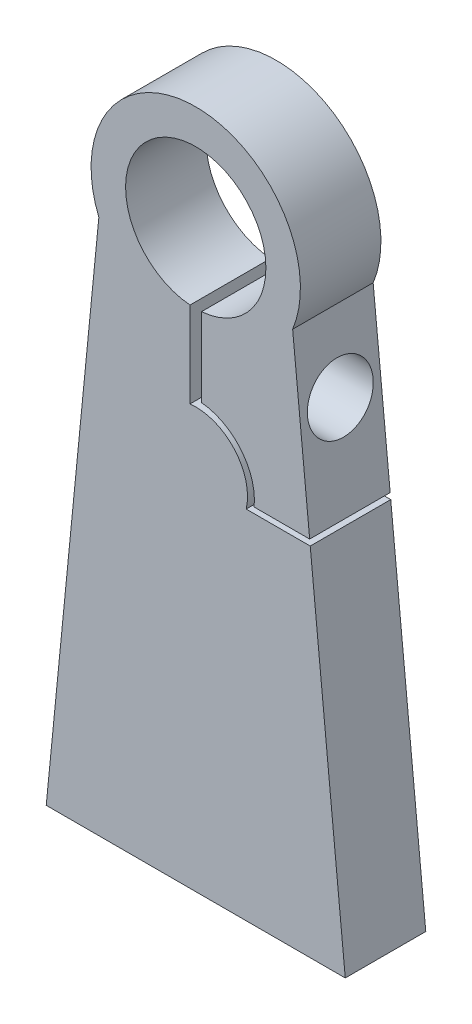
SolidWorks part; units mm, degrees
ref_plane "Front Plane" through (0, 0, 0) normal (0, 0, 1) x (1, 0, 0)
ref_plane "Top Plane" through (0, 0, 0) normal (0, 1, 0) x (1, 0, 0)
ref_plane "Right Plane" through (0, 0, 0) normal (1, 0, 0) x (0, 0, -1)
sketch "Sketch1" plane through (0, 0, 0) normal (0, 0, 1) x (1, 0, 0)
  line L0 (-13, -50) -> (13, -50)
  line L1 (-13, -50) -> (-8.4243, -3.441)
  line L2 (13, -50) -> (8.4243, -3.441)
  arc A0 (-8.4243, -3.441) -> (8.4243, -3.441) centre (0, 0) cw
  circle A1 centre (0, 0) radius 6.1
  dimension "D1" = 12.2
  dimension "D3" = 9.1
  dimension "D2" = 26
  dimension "D5" = 50
extrude "Thickness" add sketch "Sketch1" along normal mid plane 7
sketch "Sketch2" plane through (0, -50, 0) normal (0, -1, 0) x (1, 0, 0)
  line L0 (44.2539, 0) -> (-44.2539, 0) construction
  line L4 (-10.7909, 0) -> (-9.1454, -2.85)
  line L5 (-9.1454, -2.85) -> (-5.8546, -2.85)
  line L6 (-5.8546, -2.85) -> (-4.2091, 0)
  line L14 (4.2091, 0) -> (5.8546, -2.85)
  line L15 (5.8546, -2.85) -> (9.1454, -2.85)
  line L16 (9.1454, -2.85) -> (10.7909, 0)
  line L17 (0, -44.7868) -> (0, 44.7868) construction
  line L18 (4.2091, 0) -> (4.2091, 2.85)
  line L19 (4.2091, 2.85) -> (10.7909, 2.85)
  line L20 (10.7909, 2.85) -> (10.7909, 0)
  line L21 (-10.7909, 0) -> (-10.7909, 2.85)
  line L22 (-10.7909, 2.85) -> (-4.2091, 2.85)
  line L23 (-4.2091, 2.85) -> (-4.2091, 0)
  circle A0 centre (-7.5, 0) radius 2.85
  circle A1 centre (7.5, 0) radius 2.85
  dimension "D2" = 7.5
  dimension "D1" = 5.7
  dimension "D3" = 15
extrude "BotNutCut" cut sketch "Sketch2" against normal blind 2.6 from offset 2 contours A0 | A0 L22 L21 L4 | A0 L6 L23 L22 | A0 L5 L6 | A0 L4 L5 | A1 L14 L15 | A1 L15 L16 | A1 L16 L20 L19 | A1 L19 L18 L14 | A1 offset against normal yes
sketch "Sketch3" plane through (0, -50, 0) normal (0, -1, 0) x (1, 0, 0)
  line L0 (44.2539, 0) -> (-44.2539, 0) construction
  line L1 (0, -44.7868) -> (0, 44.7868) construction
  circle A0 centre (-7.5, 0) radius 1.55
  circle A1 centre (7.5, 0) radius 1.55
  dimension "D3" = 3.1
  dimension "D1" = 15
  dimension "D2" = 7.5
extrude "BotScrewCut" cut sketch "Sketch3" against normal blind 2
sketch "Sketch5" plane through (0, 0, 3.5) normal (0, 0, 1) x (1, 0, 0)
  line L0 (-0.5, -6.0795) -> (-0.5, -14)
  line L1 (-0.5, -14) -> (0.5, -14)
  line L2 (0.5, -14) -> (0.5, -6.0795)
  line L3 (0, -44.7868) -> (0, 44.7868) construction
  line L6 (55, 0) -> (-55, 0) construction
  circle A0 centre (0, 0) radius 6.1 construction
  circle A1 centre (0, -18) radius 5.1
  circle M9 centre (0, 0) radius 6.1
  dimension "D5" = 10.2
  dimension "D1" = 1
  dimension "D2" = 0.5
  dimension "D3" = 18
  dimension "D4" = 14
extrude "Cut-Extrude1" cut sketch "Sketch5" against normal up to surface (7 mm away) contours A1 L2 L0 M9
sketch "Sketch6" plane through (-0.5, 0, 0) normal (1, 0, 0) x (0, 0, -1)
  line L0 (0, 44.2539) -> (0, -44.2539) construction
  line L4 (0, -13.2909) -> (2.85, -11.6454)
  line L5 (2.85, -11.6454) -> (2.85, -8.3546)
  line L6 (2.85, -8.3546) -> (0, -6.7091)
  line L8 (0, -6.7091) -> (-2.85, -8.3546) [skipped]
  line L9 (-2.85, -8.3546) -> (-2.85, -11.6454) [skipped]
  line L10 (-2.85, -11.6454) -> (0, -13.2909) [skipped]
  line L11 (0, -6.7091) -> (-2.85, -6.7091)
  line L12 (-2.85, -6.7091) -> (-2.85, -13.2909)
  line L13 (-2.85, -13.2909) -> (0, -13.2909)
  line L14 (55, 0) -> (-55, 0) construction
  circle A0 centre (0, -10) radius 2.85 construction
  dimension "D1" = 5.7
  dimension "D2" = 10
extrude "RailNutCut" cut sketch "Sketch6" against normal blind 2.6 from offset 2 offset against normal yes
sketch "Sketch7" plane through (-0.5, 0, 0) normal (1, 0, 0) x (0, 0, -1)
  line L0 (0, 44.2539) -> (0, -44.2539) construction
  line L1 (55, 0) -> (-55, 0) construction
  circle A0 centre (0, -10) radius 1.55
  dimension "D1" = 3.1
  dimension "D2" = 10
extrude "RailScrewCut" cut sketch "Sketch7" against normal blind 2.6 and the other way up to surface other way up to face at (10.7122, -26.7205, 0)
sketch "Sketch8" plane through (0.5, 0, 0) normal (-1, 0, 0) x (0, 0, 1)
  line L0 (0, -44.2539) -> (0, 44.2539) construction
  line L1 (55, 0) -> (-55, 0) construction
  circle A0 centre (0, -10) radius 2.85
  dimension "D2" = 5.7
  dimension "D1" = 10
extrude "RailNutHeadCut" cut sketch "Sketch8" against normal up to surface (6.349 mm away) from offset 2.5 offset against normal yes
sketch "Sketch9" plane through (0, 0, 3.5) normal (0, 0, 1) x (1, 0, 0)
  line L0 (55, 0) -> (-55, 0) construction
  line L1 (4, -18.5) -> (11, -18.5)
  line L2 (4, -18.5) -> (4, -19)
  line L3 (4, -19) -> (11, -19)
  line L4 (11, -18.5) -> (11, -19)
  line L5 (0, -44.7868) -> (0, 44.7868) construction
  dimension "D1" = 18.5
  dimension "D2" = 0.5
  dimension "D3" = 7
  dimension "D4" = 4
extrude "MovementCut" cut sketch "Sketch9" against normal up to surface (7 mm away) up to face at (0, -9.001, -3.5)
sketch "Sketch10" plane through (0, 0, 0) normal (0, 0, 1) x (1, 0, 0)
  line L0 (55, 0) -> (-55, 0) construction
  line L2 (0, -44.7868) -> (0, 44.7868) construction
  line L3 (-0.5, -12.9246) -> (-0.5, -13.5279)
  line L4 (5.001, -19) -> (4.3875, -19)
  circle A0 centre (0, -18) radius 4.5
  arc A1 (-0.5, -12.9246) -> (5.001, -19) centre (0, -18) ccw
  arc A3 (-0.5, -12.9246) -> (5.001, -19) centre (0, -18) ccw construction
  dimension "D1" = 9
  dimension "D2" = 18
extrude "Boss-Extrude1" add sketch "Sketch10" along normal mid plane 7 contours L3 A1 L4 A0 | A0
equation "\"Width\"=26"
equation "\"D2@Sketch1\"=\"Width\""
equation "\"fastenWid\"=15"
equation "\"NutDiam\"= 5.7"
equation "\"D1@Sketch3\"=\"fastenWid\""
equation "\"D2@Sketch3\"=\"fastenWid\"/2"
equation "\"ScrewDiam\"=3.1"
equation "\"D3@Sketch3\"=\"ScrewDiam\""
equation "\"ScrewDepth\"=2"
equation "\"D1@BotScrewCut\" = \"ScrewDepth\""
equation "\"D19@BotNutCut\" = \"ScrewDepth\""
equation "\"NutHeight\"=2.6"
equation "\"D1@BotNutCut\" = \"NutHeight\""
equation "\"Thick\"=7"
equation "\"D1@Thickness\" = \"Thick\""
equation "\"RailHeight\"=50"
equation "\"D5@Sketch1\"=\"RailHeight\""
equation "\"RailDiam\"=12.2"
equation "\"D1@Sketch1\"=\"RailDiam\""
equation "\"D3@Sketch1\"=\"RailDiam\"/2 +3"
equation "\"D1@Sketch7\"=\"ScrewDiam\""
equation "\"D1@Sketch2\"=\"NutDiam\""
equation "\"D2@Sketch2\"=\"fastenWid\"/2"
equation "\"D3@Sketch2\"=\"fastenWid\""
equation "\"MovementCut\"=0.5"
equation "\"D2@Sketch9\"=\"MovementCut\""
equation "\"D1@Sketch9\"=\"MovementCut\" +18"
equation "\"D1@Boss-Extrude1\"=\"Thick\""
